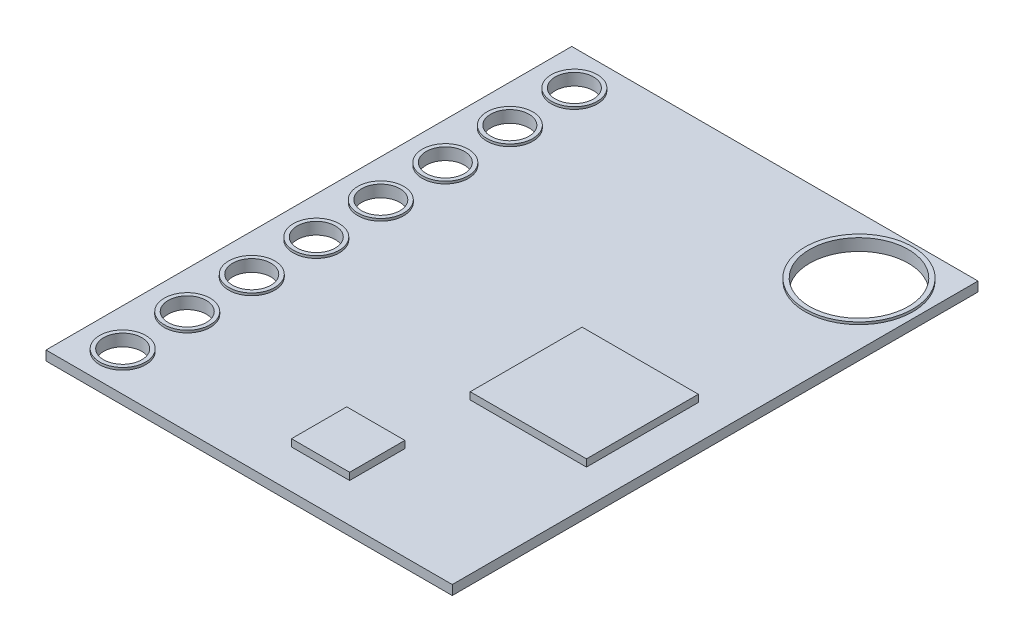
SolidWorks part; units mm, degrees
ref_plane "Front Plane" through (0, 0, 0) normal (0, 0, 1) x (1, 0, 0)
ref_plane "Top Plane" through (0, 0, 0) normal (0, 1, 0) x (1, 0, 0)
ref_plane "Right Plane" through (0, 0, 0) normal (1, 0, 0) x (0, 0, -1)
other "Center of Mass"
sketch "Sketch1" plane through (0, 0, 0) normal (0, 1, 0) x (1, 0, 0)
  line L1 (-10.6567, 9.5149) -> (6.3433, 9.5149)
  line L2 (-10.6567, 9.5149) -> (-10.6567, -12.4851)
  line L3 (-10.6567, -12.4851) -> (6.3433, -12.4851)
  line L4 (6.3433, 9.5149) -> (6.3433, -12.4851)
  circle A0 centre (3.8433, 7.0342) radius 2.0666
  circle A1 centre (-8.9984, 7.9664) radius 0.8
  circle A2 centre (-8.9984, 5.2664) radius 0.8
  circle A3 centre (-8.9984, 2.5664) radius 0.8
  circle A4 centre (-8.9984, -0.1336) radius 0.8
  circle A5 centre (-8.9984, -2.8336) radius 0.8
  circle A6 centre (-8.9984, -5.5336) radius 0.8
  circle A7 centre (-8.9984, -8.2336) radius 0.8
  circle A8 centre (-8.9984, -10.9336) radius 0.8
  dimension "D4" = 1.6
  dimension "D1" = 17
  dimension "D2" = 22
  dimension "D3" = 2.5
  dimension "D5" = 8
extrude "Boss-Extrude2" add sketch "Sketch1" along normal blind 0.4
sketch "Sketch3" plane through (0, 0.4, 0) normal (0, 1, 0) x (1, 0, 0)
  circle A0 centre (3.8433, 7.0342) radius 2.0666
  circle A1 centre (3.8433, 7.0342) radius 2.2536
  circle A2 centre (-8.9984, 7.9664) radius 0.8
  circle A3 centre (-8.9984, 7.9664) radius 0.9629
  circle A4 centre (-8.9984, 5.2664) radius 0.8
  circle A5 centre (-8.9984, 5.2664) radius 0.9629
  circle A6 centre (-8.9984, 2.5664) radius 0.8
  circle A7 centre (-8.9984, 2.5664) radius 0.9629
  circle A8 centre (-8.9984, -0.1336) radius 0.8
  circle A9 centre (-8.9984, -0.1336) radius 0.9629
  circle A10 centre (-8.9984, -2.8336) radius 0.8
  circle A11 centre (-8.9984, -2.8336) radius 0.9629
  circle A12 centre (-8.9984, -5.5336) radius 0.8
  circle A13 centre (-8.9984, -5.5336) radius 0.9629
  circle A14 centre (-8.9984, -8.2336) radius 0.8
  circle A15 centre (-8.9984, -8.2336) radius 0.9629
  circle A16 centre (-8.9984, -10.9336) radius 0.8
  circle A17 centre (-8.9984, -10.9336) radius 0.9629
  dimension "D1" = 8
extrude "Boss-Extrude3" add sketch "Sketch3" along normal blind 0.1
sketch "Sketch4" plane through (0, 0.4, 0) normal (0, 1, 0) x (1, 0, 0)
  line L1 (-2.0047, -10.8637) -> (0.4274, -10.8637)
  line L2 (-2.0047, -10.8637) -> (-2.0047, -8.5533)
  line L3 (-2.0047, -8.5533) -> (0.4274, -8.5533)
  line L4 (0.4274, -10.8637) -> (0.4274, -8.5533)
  line L5 (-2.0047, -10.8637) -> (0.4274, -8.5533) construction
  line L6 (-2.0047, -8.5533) -> (0.4274, -10.8637) construction
  line L7 (0.0321, -5.422) -> (4.8963, -5.422)
  line L8 (0.0321, -5.422) -> (0.0321, -0.7403)
  line L9 (0.0321, -0.7403) -> (4.8963, -0.7403)
  line L10 (4.8963, -5.422) -> (4.8963, -0.7403)
  line L11 (0.0321, -5.422) -> (4.8963, -0.7403) construction
  line L12 (0.0321, -0.7403) -> (4.8963, -5.422) construction
  point P0 (-0.7887, -9.7085)
  point P5 (2.4642, -3.0811)
extrude "Boss-Extrude4" add sketch "Sketch4" along normal blind 0.3
